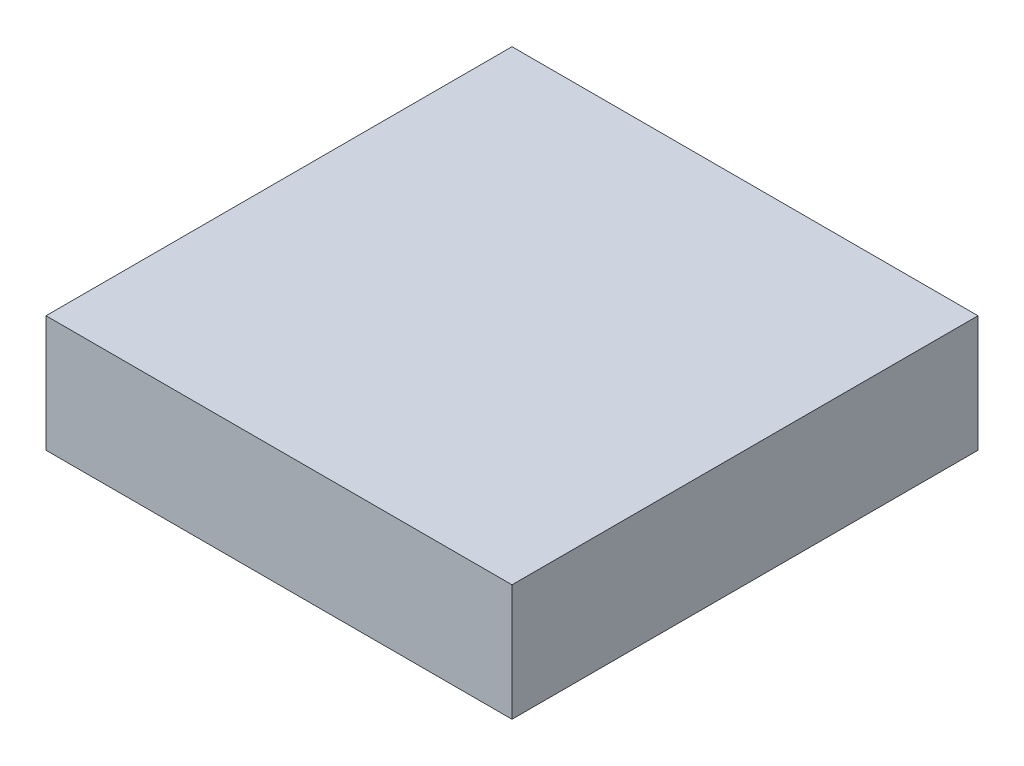
SolidWorks part; units mm, degrees
ref_plane "Front Plane" through (0, 0, 0) normal (0, 0, 1) x (1, 0, 0)
ref_plane "Top Plane" through (0, 0, 0) normal (0, 1, 0) x (1, 0, 0)
ref_plane "Right Plane" through (0, 0, 0) normal (1, 0, 0) x (0, 0, -1)
sketch "Sketch1" plane through (0, 0, 0) normal (0, 1, 0) x (1, 0, 0)
  line L1 (0, 0) -> (40, 0)
  line L2 (0, 0) -> (0, 40)
  line L3 (0, 40) -> (40, 40)
  line L4 (40, 0) -> (40, 40)
  dimension "D1" = 40
  dimension "D2" = 40
extrude "Boss-Extrude1" add sketch "Sketch1" along normal blind 10
sketch "Sketch2" plane through (0, 0, 0) normal (0, -1, 0) x (1, 0, 0)
  line L1 (14.5, -25.5) -> (25.5, -25.5)
  line L2 (14.5, -25.5) -> (14.5, -14.5)
  line L3 (14.5, -14.5) -> (25.5, -14.5)
  line L4 (25.5, -25.5) -> (25.5, -14.5)
  line L5 (14.5, -25.5) -> (25.5, -14.5) construction
  line L6 (14.5, -14.5) -> (25.5, -25.5) construction
  line L8 (40, 0) -> (40, -40) construction
  line L9 (40, -40) -> (0, -40) construction
  point P0 (20, -20)
  point P5 (20, -20)
  dimension "D1" = 11
  dimension "D2" = 11
  dimension "D3" = 20
  dimension "D4" = 20
extrude "Boss-Extrude2" add sketch "Sketch2" along normal blind 0.5
